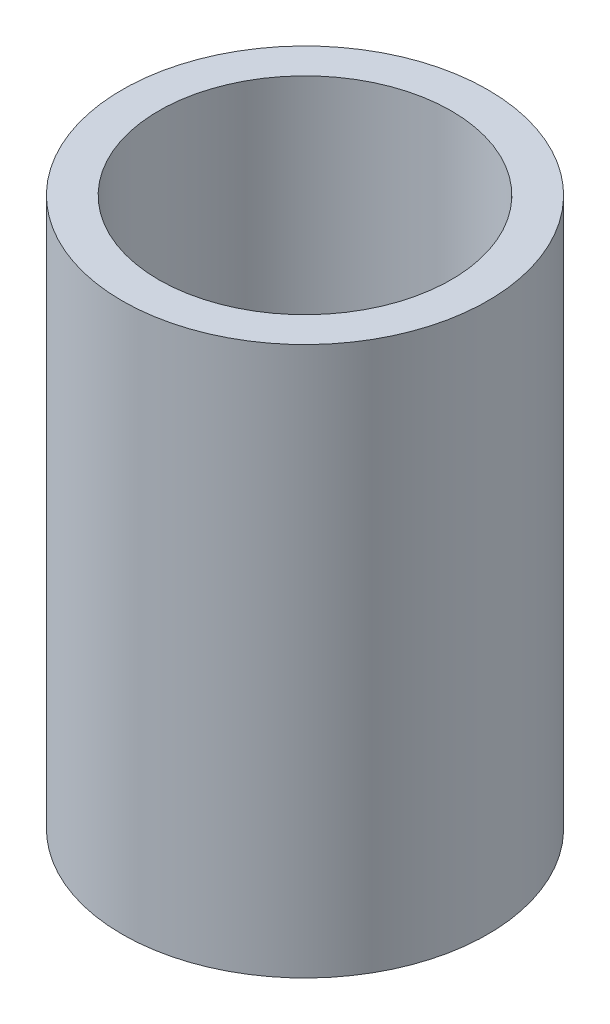
SolidWorks part; units mm, degrees
ref_plane "Front Plane" through (0, 0, 0) normal (0, 0, 1) x (1, 0, 0)
ref_plane "Top Plane" through (0, 0, 0) normal (0, 1, 0) x (1, 0, 0)
ref_plane "Right Plane" through (0, 0, 0) normal (1, 0, 0) x (0, 0, -1)
sketch "Sketch2" plane through (0, 0, 0) normal (0, 1, 0) x (1, 0, 0)
  circle A0 centre (0, 0) radius 5
  dimension "D1" = 10
extrude "Boss-Extrude1" add sketch "Sketch2" along normal blind 15
sketch "Sketch3" plane through (0, 15, 0) normal (0, 1, 0) x (1, 0, 0)
  circle A0 centre (0, 0) radius 4
  dimension "D1" = 8
extrude "Cut-Extrude1" cut sketch "Sketch3" against normal offset from surface (13 mm away) 2 up to face at (0, 0, 5)
